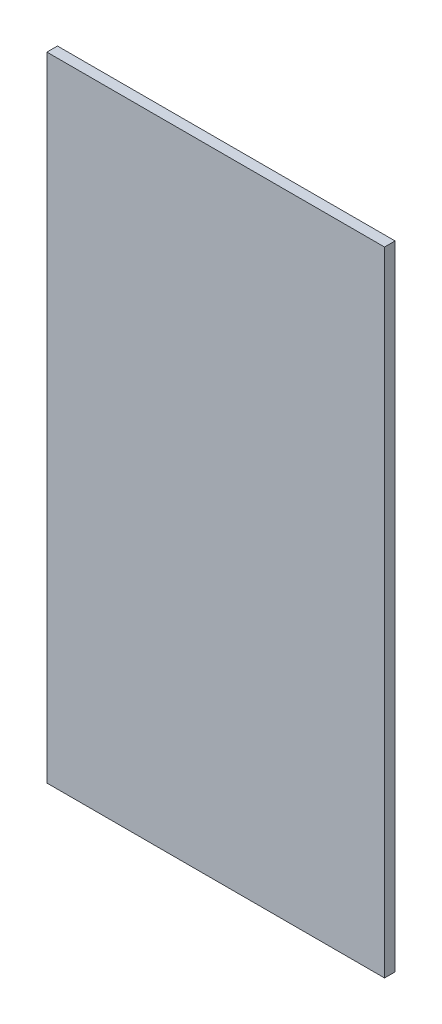
SolidWorks part; units mm, degrees
ref_plane "Front Plane" through (0, 0, 0) normal (0, 0, 1) x (1, 0, 0)
ref_plane "Top Plane" through (0, 0, 0) normal (0, 1, 0) x (1, 0, 0)
ref_plane "Right Plane" through (0, 0, 0) normal (1, 0, 0) x (0, 0, -1)
sketch "Sketch1" plane through (0, 0, 0) normal (0, 0, 1) x (1, 0, 0)
  line L1 (-514.8896, -291.1897) -> (-311.6896, -291.1897)
  line L2 (-514.8896, -291.1897) -> (-514.8896, -672.1897)
  line L3 (-514.8896, -672.1897) -> (-311.6896, -672.1897)
  line L4 (-311.6896, -291.1897) -> (-311.6896, -672.1897)
  dimension "D1" = 203.2
  dimension "D2" = 381
extrude "Boss-Extrude2" add sketch "Sketch1" along normal blind 6.35
